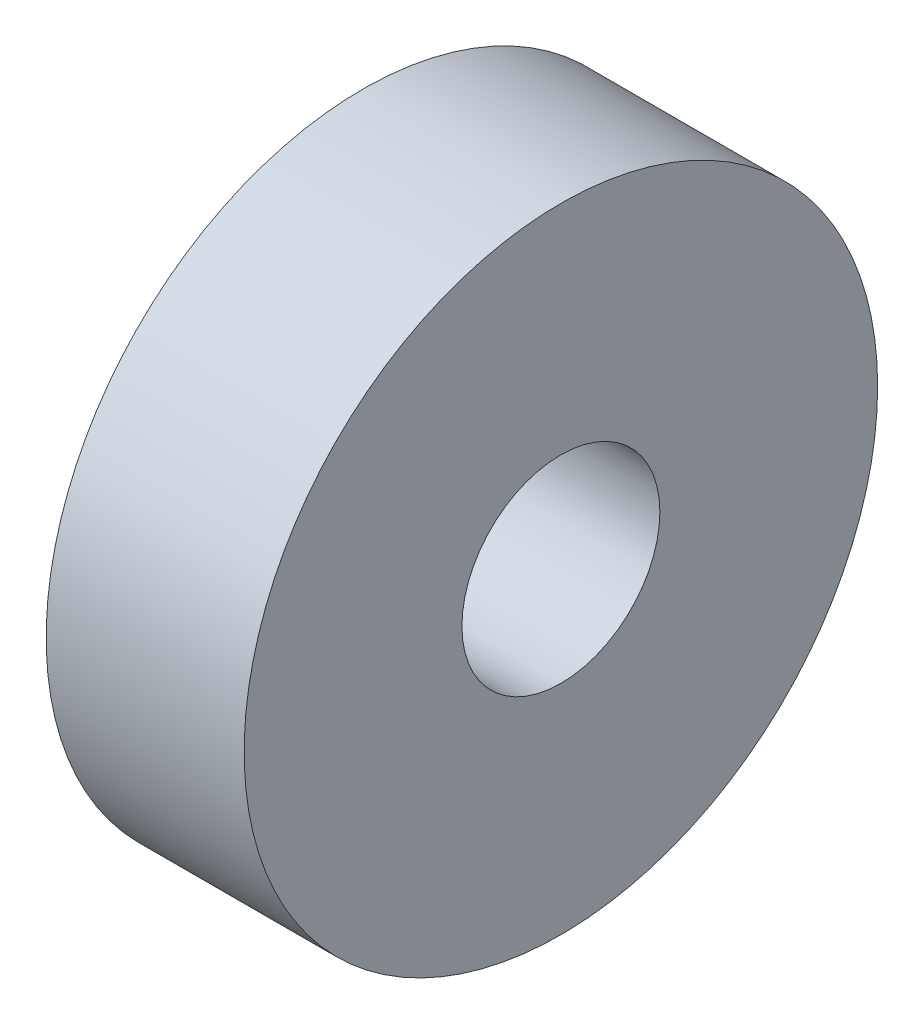
SolidWorks part; units mm, degrees
ref_plane "Front Plane" through (0, 0, 0) normal (0, 0, 1) x (1, 0, 0)
ref_plane "Top Plane" through (0, 0, 0) normal (0, 1, 0) x (1, 0, 0)
ref_plane "Right Plane" through (0, 0, 0) normal (1, 0, 0) x (0, 0, -1)
other "Configuration Table"
sketch "Sketch1" plane through (0, 0, 0) normal (1, 0, 0) x (0, 0, -1)
  circle A0 centre (0, 0) radius 8
  circle A1 centre (0, 0) radius 2.5
  dimension "D1" = 5
  dimension "D2" = 16
extrude "Boss-Extrude1" add sketch "Sketch1" along normal blind 5
